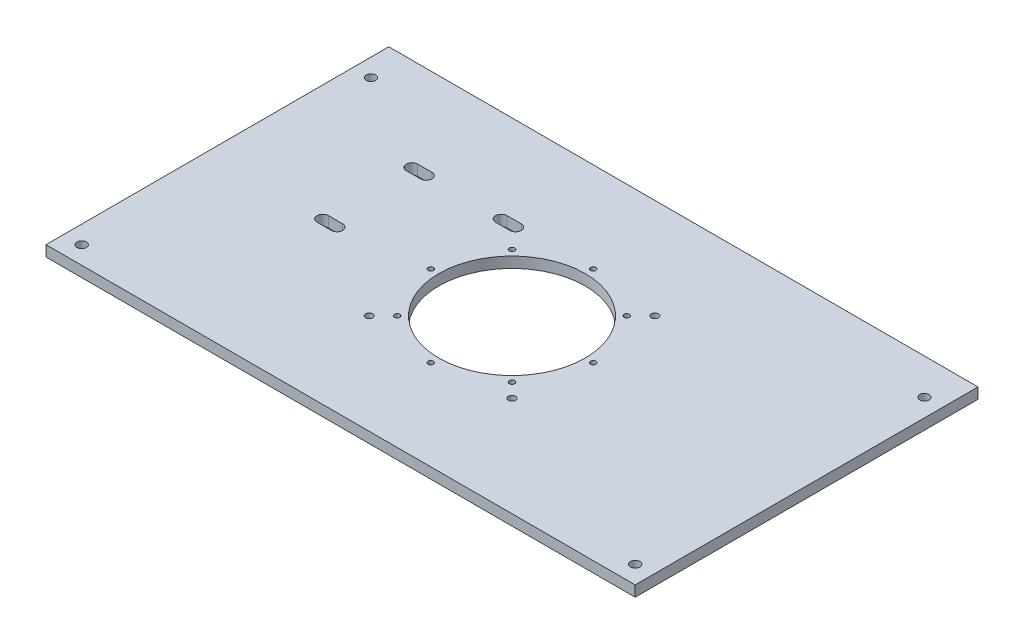
SolidWorks part; units mm, degrees
ref_plane "Front Plane" through (0, 0, 0) normal (0, 0, 1) x (1, 0, 0)
ref_plane "Top Plane" through (0, 0, 0) normal (0, 1, 0) x (1, 0, 0)
ref_plane "Right Plane" through (0, 0, 0) normal (1, 0, 0) x (0, 0, -1)
sketch "Sketch1" plane through (0, 0, 0) normal (0, 1, 0) x (1, 0, 0)
  line L1 (0, 0) -> (330, 0)
  line L2 (0, 0) -> (0, 192)
  line L3 (0, 192) -> (330, 192)
  line L4 (330, 0) -> (330, 192)
  dimension "D1" = 192
  dimension "D2" = 330
extrude "Boss-Extrude1" add sketch "Sketch1" along normal blind 6
sketch "Sketch2" plane through (0, 6, 0) normal (0, 1, 0) x (1, 0, 0)
  line L0 (0, 0) -> (330, 0) construction
  line L1 (0, 0) -> (0, 192)
  circle A0 centre (165, 96) radius 50 construction
  circle A1 centre (165, 96) radius 45.5 construction
  circle A2 centre (165, 141.5) radius 1.5
  circle A3 centre (197.1734, 128.1734) radius 1.5
  circle A4 centre (210.5, 96) radius 1.5
  circle A5 centre (197.1734, 63.8266) radius 1.5
  circle A6 centre (165, 50.5) radius 1.5
  circle A7 centre (132.8266, 63.8266) radius 1.5
  circle A8 centre (119.5, 96) radius 1.5
  circle A9 centre (132.8266, 128.1734) radius 1.5
  point P21 (165, 96)
  dimension "D1" = 100
  dimension "D2" = 91
  dimension "D3" = 3
  dimension "D5" = 192
  dimension "D6" = 330
  dimension "D4" = 8
extrude "Cut-Extrude1" cut sketch "Sketch2" against normal through all and the other way through all contours A2 | A3 | A4 | A6 | A7 | A8 | A9 | A5
sketch "Sketch3" plane through (0, 6, 0) normal (0, 1, 0) x (1, 0, 0)
  line L0 (0, 0) -> (0, 192)
  line L1 (0, 0) -> (330, 0)
  line L2 (0, 0) -> (330, 0) construction
  circle A0 centre (165, 96) radius 41
  dimension "D1" = 82
  dimension "D2" = 330
  dimension "D3" = 192
extrude "Cut-Extrude2" cut sketch "Sketch3" against normal through all contours A0
sketch "Sketch4" plane through (0, 6, 0) normal (0, 1, 0) x (1, 0, 0)
  line L0 (165, 96) -> (208.759, 133.3015) construction
  line L1 (165, 96) -> (165, 153.5) construction
  line L2 (165, 96) -> (187.0043, 149.1231) construction
  circle A0 centre (165, 96) radius 57.5 construction
  circle A1 centre (187.0043, 149.1231) radius 3
  circle A2 centre (224.1231, 73.9957) radius 3
  circle A3 centre (148.9957, 36.8769) radius 3
  circle A4 centre (111.8769, 112.0043) radius 3
  point P16 (168, 93)
  dimension "D1" = 115
  dimension "D2" = 22.5
  dimension "D3" = 6
  dimension "D4" = 4
extrude "Cut-Extrude3" [suppressed] cut sketch "Sketch4" against normal blind 10
sketch "Sketch7" plane through (0, 0, 0) normal (0, -1, 0) x (1, 0, 0)
  line L0 (0, 0) -> (0, -115) construction
  line L1 (0, -192) -> (0, 0) construction
  line L2 (0, -115) -> (93, -115) construction
  circle A0 centre (93, -115) radius 3
  dimension "D3" = 6
  dimension "D1" = 115
  dimension "D2" = 93
extrude "Cut-Extrude4" [suppressed] cut sketch "Sketch7" against normal blind 10
hole_wizard "Tap Drill for M6 Helicoil1" [suppressed] positions "Sketch8" profile "Sketch9" hole size "M6x1.0" standard "DIN"
sketch "Sketch8" [suppressed] plane through (0, 0, 0) normal (0, -1, 0) x (-1, 0, 0)
  line L1 (-63, 85) -> (-123, 85)
  line L2 (-63, 85) -> (-63, 145)
  line L3 (-63, 145) -> (-123, 145)
  line L4 (-123, 85) -> (-123, 145)
  line L5 (-63, 85) -> (-123, 145) construction
  line L6 (-63, 145) -> (-123, 85) construction
  point P1 (-93, 115)
  dimension "D1" = 60
sketch "Sketch9" plane through (93, 0, -115) normal (1, 0, 0) x (0, 0, -1)
  line L0 (0, 0) -> (0, 13.8177)
  line L1 (0, 13.8177) -> (3.125, 11.94)
  line L2 (3.125, 11.94) -> (3.125, 0)
  line L5 (3.125, 0) -> (0, 0)
  line L10 (0, 13.8177) -> (-3.125, 11.94) construction
  line L11 (0, -6.35) -> (0, 107.95) construction
  dimension "Hole Dia." = 6.25
  dimension "Hole Depth" = 11.94
  dimension "Drill Angle" = 118
sketch "Sketch10" plane through (0, 0, 0) normal (0, -1, 0) x (1, 0, 0)
  line L0 (330, -192) -> (0, -192) construction
  line L1 (123, -140) -> (73, -140) construction
  line L2 (123, -140) -> (123, -90) construction
  line L3 (123, -90) -> (73, -90) construction
  line L4 (73, -140) -> (73, -90) construction
  line L5 (123, -140) -> (73, -90) construction
  line L6 (123, -90) -> (73, -140) construction
  line L7 (0, -192) -> (0, 0) construction
  line L8 (73, -90) -> (65, -90) construction
  line L9 (73, -93.2) -> (65, -93.2)
  line L10 (73, -86.8) -> (65, -86.8)
  line L11 (73, -140) -> (65, -140) construction
  line L12 (73, -143.2) -> (65, -143.2)
  line L13 (73, -136.8) -> (65, -136.8)
  line L14 (123, -140) -> (115, -140) construction
  line L15 (123, -143.2) -> (115, -143.2)
  line L16 (123, -136.8) -> (115, -136.8)
  arc A0 (73, -93.2) -> (73, -86.8) centre (73, -90) ccw
  arc A1 (73, -143.2) -> (73, -136.8) centre (73, -140) ccw
  arc A2 (123, -143.2) -> (123, -136.8) centre (123, -140) ccw
  arc A3 (73, -93.2) -> (73, -86.8) centre (73, -90) ccw
  arc A4 (65, -86.8) -> (65, -93.2) centre (65, -90) ccw
  arc A5 (73, -143.2) -> (73, -136.8) centre (73, -140) ccw
  arc A6 (65, -136.8) -> (65, -143.2) centre (65, -140) ccw
  arc A7 (123, -143.2) -> (123, -136.8) centre (123, -140) ccw
  arc A8 (115, -136.8) -> (115, -143.2) centre (115, -140) ccw
  point P0 (98, -115)
  point P13 (69, -90)
  point P19 (69, -140)
  point P25 (119, -140)
  point P37 (98, -115)
  dimension "D2" = 6.4
  dimension "D3" = 6.4
  dimension "D4" = 6.4
  dimension "D5" = 77
  dimension "D6" = 98
  dimension "D7" = 8
extrude "Cut-Extrude5" cut sketch "Sketch10" against normal blind 10 contours L16 A8 L15 A2 | L13 A6 L12 A1 | L10 A4 L9 A0
sketch "Sketch11" plane through (0, 0, 0) normal (0, -1, 0) x (1, 0, 0)
  line L5 (125, -136) -> (205, -136) construction
  line L11 (125, -136) -> (125, -56) construction
  line L12 (125, -56) -> (205, -56) construction
  line L13 (205, -136) -> (205, -56) construction
  line L14 (125, -136) -> (205, -56)
  line L15 (125, -56) -> (205, -136)
  circle A4 centre (125, -56) radius 2
  circle A5 centre (205, -56) radius 2
  circle A6 centre (205, -136) radius 2
  point P0 (165, -96)
  dimension "D3" = 4
  dimension "D1" = 80
  dimension "D2" = 80
extrude "Cut-Extrude6" cut sketch "Sketch11" against normal blind 10
hole_wizard "M5 Clearance Hole1" positions "Sketch13" profile "Sketch14" hole size "M5" standard "DIN"
sketch "Sketch13" plane through (0, 6, 0) normal (0, 1, 0) x (1, 0, 0)
  line L0 (0, 192) -> (0, 0) construction
  line L1 (330, 0) -> (330, 192) construction
  line L2 (10, 172) -> (320, 172) construction
  line L3 (320, 172) -> (320, 10) construction
  line L4 (320, 10) -> (10, 10) construction
  line L5 (10, 10) -> (10, 172) construction
  line L15 (330, 192) -> (0, 192) construction
  point P0 (10, 172)
  point P2 (10, 10)
  point P4 (320, 10)
  point P6 (320, 172)
  dimension "D1" = 10
  dimension "D2" = 10
  dimension "D3" = 10
  dimension "D4" = 10
  dimension "D5" = 162
  dimension "D6" = 162
  dimension "D7" = 20
sketch "Sketch14" plane through (10, 6, -172) normal (1, 0, 0) x (0, 0, 1)
  line L0 (0, 0) -> (0, 13.5323)
  line L1 (0, 13.5323) -> (2.65, 11.94)
  line L2 (2.65, 11.94) -> (2.65, 0)
  line L5 (2.65, 0) -> (0, 0)
  line L10 (0, 13.5323) -> (-2.65, 11.94) construction
  line L11 (0, -6.35) -> (0, 107.95) construction
  dimension "Hole Dia." = 5.3
  dimension "Hole Depth" = 11.94
  dimension "Drill Angle" = 118
sketch "Sketch15" [suppressed] plane through (0, 0, 0) normal (0, -1, 0) x (1, 0, 0)
  line L0 (0, 0) -> (330, 0) construction
  line L1 (0, -192) -> (10, -192)
  line L2 (0, -192) -> (0, 0)
  line L3 (0, 0) -> (10, 0)
  line L4 (10, -192) -> (10, 0)
  line L6 (330, -192) -> (320, -192)
  line L7 (330, -192) -> (330, 0)
  line L8 (330, 0) -> (320, 0)
  line L9 (320, -192) -> (320, 0)
  line L10 (10, 0) -> (320, 0)
  line L11 (10, 0) -> (10, -10)
  line L12 (10, -10) -> (320, -10)
  line L13 (320, 0) -> (320, -10)
  line L14 (320, -192) -> (10, -192)
  line L15 (320, -192) -> (320, -182)
  line L16 (320, -182) -> (10, -182)
  line L17 (10, -192) -> (10, -182)
  dimension "D1" = 10
  dimension "D2" = 10
  dimension "D3" = 10
  dimension "D4" = 10
extrude "Cut-Extrude7" [suppressed] cut sketch "Sketch15" against normal blind 0.05 contours L10 L13 L12 L11 | L4 L1 L2 L3 | L15 L16 L17 L14 | L6 L7 L8 L9
sketch "Sketch16" [suppressed] plane through (0, 6, 0) normal (0, 1, 0) x (1, 0, 0)
  circle A0 centre (165, 96) radius 41
  circle A1 centre (165, 96) radius 50
  dimension "D1" = 100
extrude "Boss-Extrude2" [suppressed] add sketch "Sketch16" along normal blind 0.05
sketch "Sketch17" [suppressed] plane through (0, 6, 0) normal (0, 1, 0) x (1, 0, 0)
  line L0 (50, 192) -> (280, 192) construction
  line L1 (330, 192) -> (0, 192) construction
  line L2 (50, 222) -> (280, 222)
  line L3 (50, 162) -> (280, 162)
  line L4 (330, 0) -> (330, 192) construction
  line L5 (0, 192) -> (0, 0) construction
  line L6 (280, 0) -> (50, 0) construction
  line L7 (0, 0) -> (330, 0) construction
  line L8 (280, -30) -> (50, -30)
  line L9 (280, 30) -> (50, 30)
  line L10 (330, 96) -> (280, 96) construction
  line L11 (330, 53.5) -> (280, 53.5)
  line L12 (330, 138.5) -> (280, 138.5)
  arc A0 (50, 222) -> (50, 162) centre (50, 192) ccw
  arc A1 (280, 162) -> (280, 222) centre (280, 192) ccw
  arc A2 (280, -30) -> (280, 30) centre (280, 0) ccw
  arc A3 (50, 30) -> (50, -30) centre (50, 0) ccw
  arc A4 (330, 53.5) -> (330, 138.5) centre (330, 96) ccw
  arc A5 (280, 138.5) -> (280, 53.5) centre (280, 96) ccw
  point P4 (165, 192)
  point P17 (165, 0)
  point P24 (305, 96)
  point P29 (305, 138.5)
  dimension "D1" = 50
  dimension "D2" = 50
  dimension "D3" = 50
  dimension "D4" = 50
  dimension "D5" = 60
  dimension "D6" = 60
  dimension "D7" = 85
  dimension "D8" = 50
extrude "Cut-Extrude8" [suppressed] cut sketch "Sketch17" against normal through all
sketch "Sketch18" [suppressed] plane through (0, 6, 0) normal (0, 1, 0) x (1, 0, 0)
  line L0 (0, 126) -> (0, 66) construction
  line L1 (0, 192) -> (0, 0) construction
  line L2 (30, 126) -> (30, 66)
  line L3 (-30, 126) -> (-30, 66)
  line L4 (0, 66) -> (0, 0) construction
  line L5 (0, 126) -> (0, 192) construction
  arc A0 (30, 126) -> (-30, 126) centre (0, 126) ccw
  arc A1 (-30, 66) -> (30, 66) centre (0, 66) ccw
  point P4 (0, 96)
  dimension "D1" = 60
  dimension "D2" = 60
extrude "Cut-Extrude9" [suppressed] cut sketch "Sketch18" against normal through all
equation "\"D2@Sketch13\"=\"D1@Sketch13\""
equation "\"D3@Sketch13\"=\"D1@Sketch13\""
equation "\"D4@Sketch13\"=\"D1@Sketch13\""
equation "\"D6@Sketch13\"=\"D5@Sketch13\""
